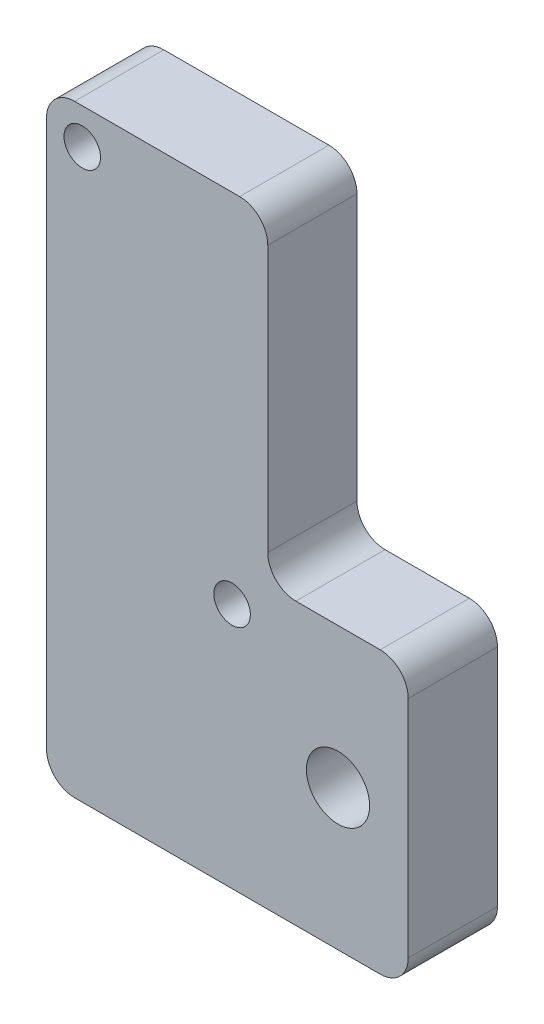
SolidWorks part; units mm, degrees
material "Balsa"
ref_plane "Front Plane" through (0, 0, 0) normal (0, 0, 1) x (1, 0, 0)
ref_plane "Top Plane" through (0, 0, 0) normal (0, 1, 0) x (1, 0, 0)
ref_plane "Right Plane" through (0, 0, 0) normal (1, 0, 0) x (0, 0, -1)
sketch "Sketch1" plane through (0, 0, 0) normal (0, 0, 1) x (1, 0, 0)
  line L0 (0, 0) -> (0, 27.94)
  line L1 (0, 27.94) -> (15.748, 27.94)
  line L2 (15.748, 27.94) -> (15.748, 5)
  line L3 (15.748, 5) -> (25.748, 5)
  line L4 (25.748, 5) -> (25.748, 0)
  line L5 (25.748, 0) -> (0, 0) construction
  line L6 (0, 0) -> (0, -15)
  line L7 (0, -15) -> (25.748, -15)
  line L8 (25.748, -15) -> (25.748, 0)
  line L9 (15.748, 5) -> (15.748, 0) construction
  line L10 (0, 25.4) -> (2.54, 25.4) construction
  line L11 (2.54, 25.4) -> (2.54, 27.94) construction
  line L13 (13.208, 0) -> (13.208, 2.54) construction
  line L14 (13.208, 2.54) -> (15.748, 2.54) construction
  circle A0 centre (20.748, -5) radius 2.25
  circle A1 centre (2.54, 25.4) radius 1.3
  circle A2 centre (13.208, 2.54) radius 1.3
  dimension "D4" = 4.5
  dimension "D6" = 5
  dimension "D9" = 2.6
  dimension "D10" = 10
  dimension "D1" = 15.748
  dimension "D2" = 27.94
  dimension "D3" = 15
  dimension "D5" = 10
  dimension "D7" = 20
  dimension "D8" = 2.54
extrude "Boss-Extrude1" add sketch "Sketch1" along normal blind 6.35
fillet "Fillet1" radius 2 6 edges at (25.748, -15, 3.175) (0, -15, 3.175) (0, 27.94, 3.175) (15.748, 27.94, 3.175) (25.748, 5, 3.175) (15.748, 5, 3.175)
